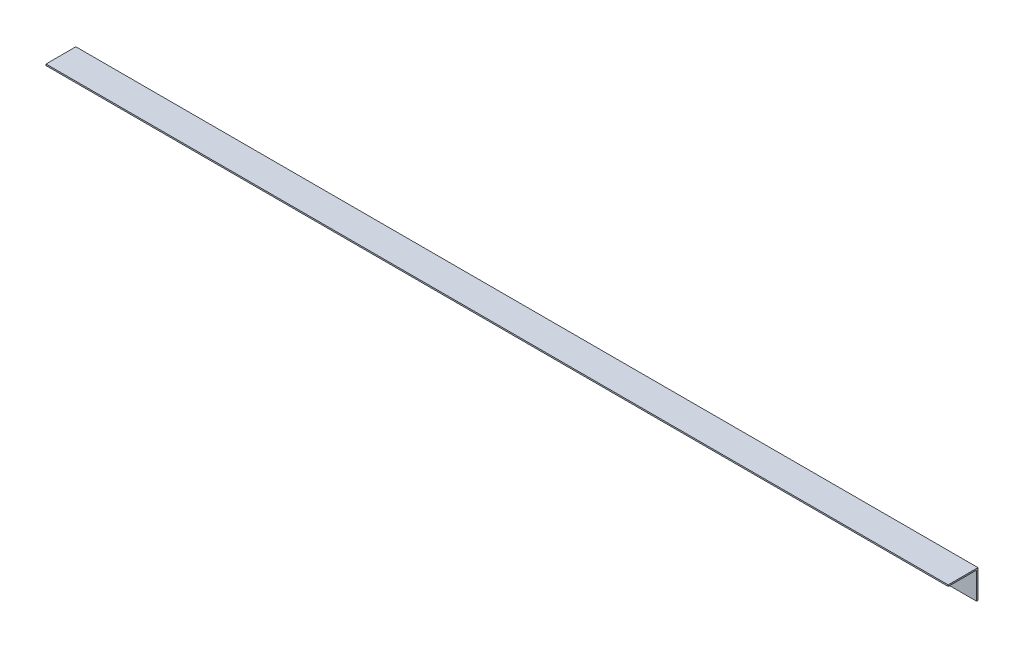
SolidWorks part; units mm, degrees
ref_plane "Plan de face" through (0, 0, 0) normal (0, 0, 1) x (1, 0, 0)
ref_plane "Plan de dessus" through (0, 0, 0) normal (0, 1, 0) x (1, 0, 0)
ref_plane "Plan de droite" through (0, 0, 0) normal (1, 0, 0) x (0, 0, -1)
sketch "Esquisse1" plane through (0, 0, 0) normal (0, 0, 1) x (1, 0, 0)
  line L1 (0, 0) -> (635, 0)
  line L2 (0, 0) -> (0, 20)
  line L3 (0, 20) -> (635, 20)
  line L4 (635, 0) -> (635, 20)
  dimension "D1" = 20
  dimension "D2" = 635
extrude "Boss.-Extru.1" add sketch "Esquisse1" along normal blind 1
sketch "Esquisse2" plane through (0, 0, 1) normal (0, 0, 1) x (1, 0, 0)
  line L0 (635, 0) -> (635, 20) construction
  line L1 (0, 20) -> (635, 20)
  line L2 (0, 20) -> (0, 19)
  line L3 (0, 19) -> (635, 19)
  line L4 (635, 20) -> (635, 19)
  dimension "D1" = 1
extrude "Boss.-Extru.2" add sketch "Esquisse2" along normal blind 20
